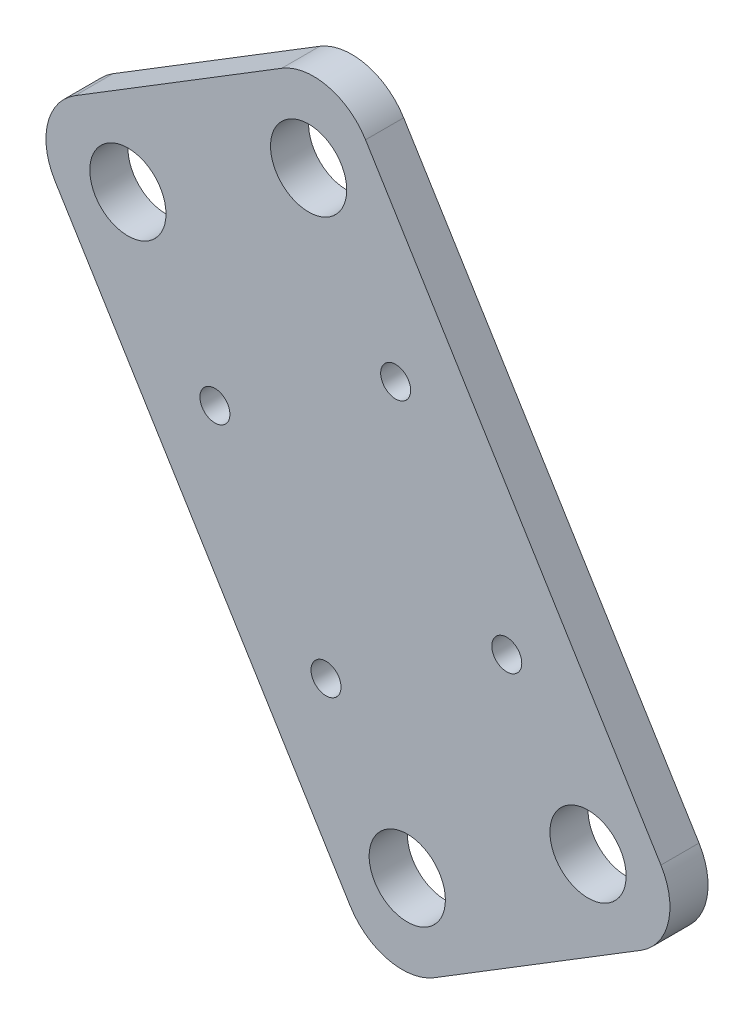
SolidWorks part; units mm, degrees
ref_plane "Front Plane" through (0, 0, 0) normal (0, 0, 1) x (1, 0, 0)
ref_plane "Top Plane" through (0, 0, 0) normal (0, 1, 0) x (1, 0, 0)
ref_plane "Right Plane" through (0, 0, 0) normal (1, 0, 0) x (0, 0, -1)
sketch "Sketch1" plane through (0, 0, 0) normal (0, 0, 1) x (1, 0, 0)
  line L0 (-86.4359, -165.6024) -> (-61.8256, -205.6323)
  line L2 (-80.1066, -132.9707) -> (-80.1066, -142.7205)
  line L6 (-109.0348, -139.5063) -> (-109.0348, -145.3991)
  line L9 (-54.8375, -207.2993) -> (-37.6144, -196.7106)
  line L10 (-35.9475, -189.7224) -> (-60.5577, -149.6925)
  line L11 (-67.5459, -148.0255) -> (-84.7689, -158.6142)
  line L12 (-58.0501, -165.8958) -> (-48.7917, -180.9551) construction
  arc A8 (-62.6351, -190.5035) -> (-65.0669, -189.9235) centre (-63.851, -190.2135) ccw
  arc A9 (-65.0669, -189.9235) -> (-62.6351, -190.5035) centre (-63.851, -190.2135) ccw
  arc A10 (-50.0076, -180.665) -> (-47.5758, -181.2451) centre (-48.7917, -180.9551) ccw
  arc A11 (-47.5758, -181.2451) -> (-50.0076, -180.665) centre (-48.7917, -180.9551) ccw
  arc A12 (-56.8342, -166.1859) -> (-59.266, -165.6058) centre (-58.0501, -165.8958) ccw
  arc A13 (-59.266, -165.6058) -> (-56.8342, -166.1859) centre (-58.0501, -165.8958) ccw
  arc A14 (-74.3253, -174.8642) -> (-71.8935, -175.4443) centre (-73.1094, -175.1542) ccw
  arc A15 (-71.8935, -175.4443) -> (-74.3253, -174.8642) centre (-73.1094, -175.1542) ccw
  circle A16 centre (-80.3613, -163.3585) radius 3.175
  circle A17 centre (-65.302, -154.1001) radius 3.175
  circle A18 centre (-42.022, -191.9663) radius 3.175
  circle A19 centre (-57.0813, -201.2247) radius 3.175
  arc A20 (-61.8256, -205.6323) -> (-54.8375, -207.2993) centre (-57.4981, -202.9717) ccw
  arc A21 (-37.6144, -196.7106) -> (-35.9475, -189.7224) centre (-40.275, -192.383) ccw
  arc A22 (-60.5577, -149.6925) -> (-67.5459, -148.0255) centre (-64.8853, -152.3531) ccw
  arc A23 (-86.4359, -165.6024) -> (-84.7689, -158.6142) centre (-82.1084, -162.9418) cw
  point P32 (0, 0)
  dimension "D6" = 6.35
  dimension "D8" = 6.35
  dimension "D10" = 6.35
  dimension "D15" = 6.35
  dimension "D16" = 5.08
  dimension "D1" = 6.35
  dimension "D3" = 6.35
  dimension "D4" = 6.35
  dimension "D5" = 6.35
  dimension "D7" = 6.35
  dimension "D9" = 6.35
  dimension "D11" = 6.35
  dimension "D12" = 6.35
  dimension "D13" = 6.35
  dimension "D14" = 6.35
extrude "Boss-Extrude1" add sketch "Sketch1" along normal blind 3.175
